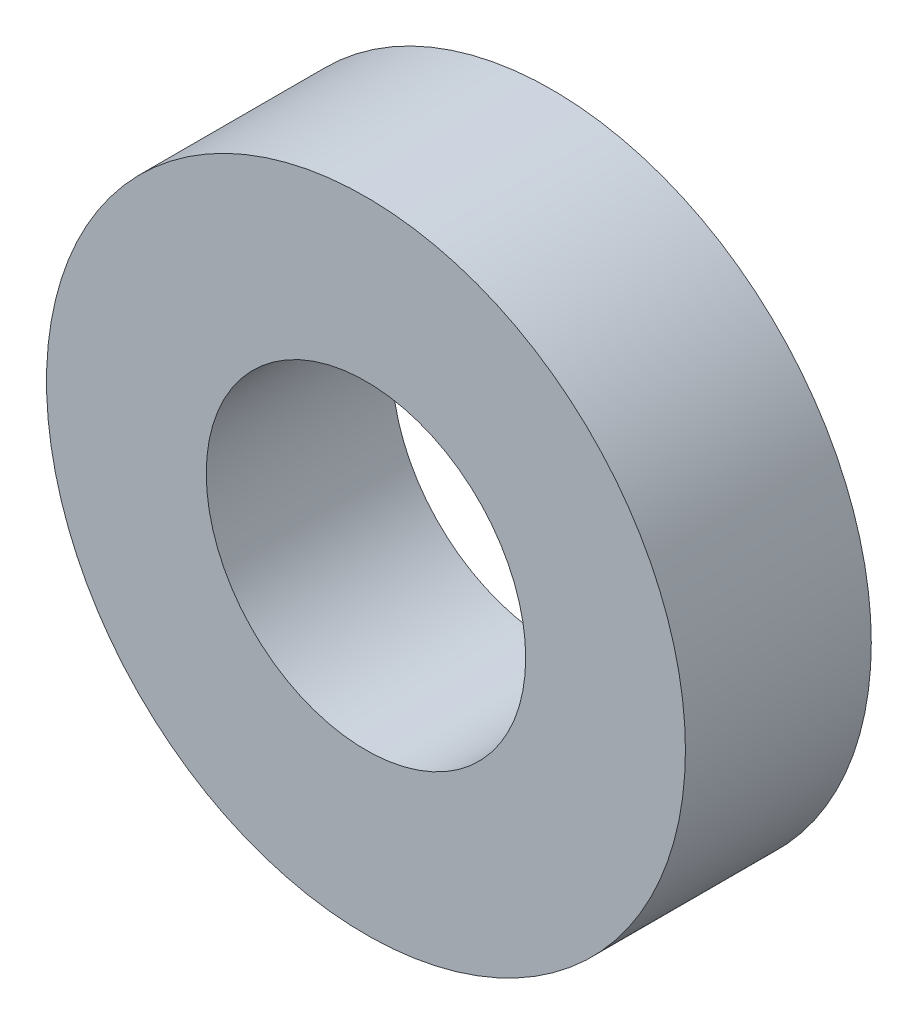
SolidWorks part; units mm, degrees
material "VITON"
ref_plane "Front Plane" through (0, 0, 0) normal (0, 0, 1) x (1, 0, 0)
ref_plane "Top Plane" through (0, 0, 0) normal (0, 1, 0) x (1, 0, 0)
ref_plane "Right Plane" through (0, 0, 0) normal (1, 0, 0) x (0, 0, -1)
sketch "BaseS" plane through (0, 0, 0) normal (0, 0, 1) x (1, 0, 0)
  circle A0 centre (0, 0) radius 5.5
  circle A1 centre (0, 0) radius 2.75
  dimension "OD" = 11
  dimension "RefDia" = 5.5
  dimension "IDControl" = 2.75
extrude "BASE" add sketch "BaseS" along normal blind 3.2
